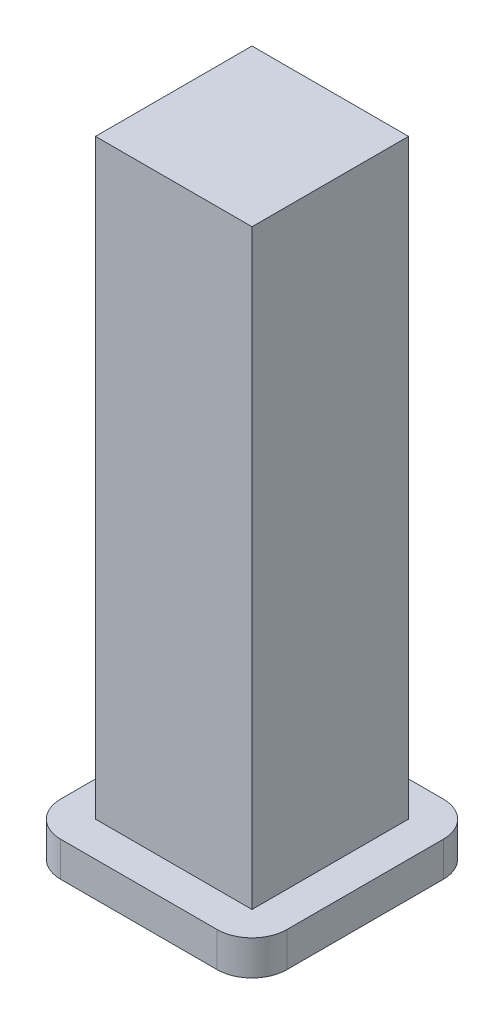
SolidWorks part; units mm, degrees
ref_plane "Front Plane" through (0, 0, 0) normal (0, 0, 1) x (1, 0, 0)
ref_plane "Top Plane" through (0, 0, 0) normal (0, 1, 0) x (1, 0, 0)
ref_plane "Right Plane" through (0, 0, 0) normal (1, 0, 0) x (0, 0, -1)
sketch "Sketch1" plane through (0, 0, 0) normal (0, 0, 1) x (1, 0, 0)
  line L1 (0, 0) -> (45, 0)
  line L2 (0, 0) -> (0, 180)
  line L3 (0, 180) -> (45, 180)
  line L4 (45, 0) -> (45, 180)
  dimension "D1" = 180
  dimension "D2" = 45
extrude "Boss-Extrude1" add sketch "Sketch1" along normal blind 45
sketch "Sketch2" plane through (0, 0, 0) normal (0, -1, 0) x (1, 0, 0)
  line L0 (0, 45) -> (45, 45) construction
  line L1 (-10, -10) -> (55, -10)
  line L2 (-10, -10) -> (-10, 55)
  line L3 (-10, 55) -> (55, 55)
  line L4 (55, -10) -> (55, 55)
  line L5 (0, 45) -> (0, 0) construction
  line L6 (45, 45) -> (45, 0) construction
  line L7 (0, 0) -> (45, 0) construction
  dimension "D1" = 10
  dimension "D2" = 10
  dimension "D3" = 10
  dimension "D4" = 10
extrude "Boss-Extrude2" add sketch "Sketch2" against normal blind 10
fillet "Fillet1" radius 10 4 edges at (-10, 5, 55) (55, 5, 55) (55, 5, -10) (-10, 5, -10)
